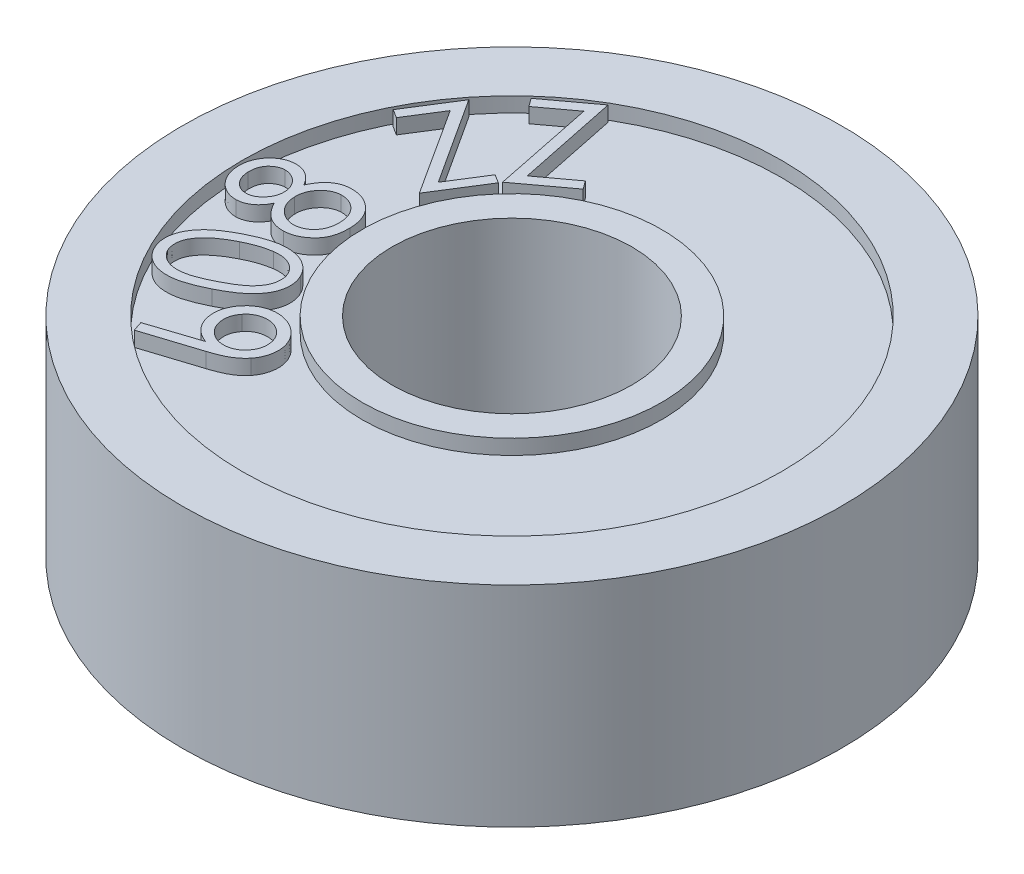
SolidWorks part; units mm, degrees
material "Bronce de aluminio"
ref_plane "Alzado" through (0, 0, 0) normal (0, 0, 1) x (1, 0, 0)
ref_plane "Planta" through (0, 0, 0) normal (0, 1, 0) x (1, 0, 0)
ref_plane "Vista lateral" through (0, 0, 0) normal (1, 0, 0) x (0, 0, -1)
sketch "Croquis1" plane through (0, 0, 0) normal (0, 1, 0) x (1, 0, 0)
  circle A0 centre (0, 0) radius 11
  circle A1 centre (0, 0) radius 9
  dimension "D1" = 22
  dimension "D2" = 18
extrude "Saliente-Extruir1" add sketch "Croquis1" along normal blind 7
sketch "Croquis2" plane through (0, 0, 0) normal (0, 1, 0) x (1, 0, 0)
  circle A0 centre (0, 0) radius 4
  circle A1 centre (0, 0) radius 5
  dimension "D1" = 8
  dimension "D2" = 10
extrude "Saliente-Extruir2" add sketch "Croquis2" along normal blind 7 separate body
sketch "Croquis3" plane through (0, 0, 0) normal (0, 1, 0) x (1, 0, 0)
  circle A0 centre (0, 0) radius 9 construction
  circle A1 centre (0, 0) radius 9
  circle A2 centre (0, 0) radius 5 construction
  circle A3 centre (0, 0) radius 5
extrude "Saliente-Extruir3" add sketch "Croquis3" along normal offset from surface (6 mm away) 0.5 from offset 0.5 separate body up to face at (0, 7, 11)
sketch "Croquis4" plane through (0, 6.5, 0) normal (0, 1, 0) x (1, 0, 0)
  circle A0 centre (0, 0) radius 5.5 construction
  text T0 "608 ZZ" font "Century Gothic" height 3.5
  dimension "D1" = 11
extrude "Saliente-Extruir4" add sketch "Croquis4" along normal blind 0.5
